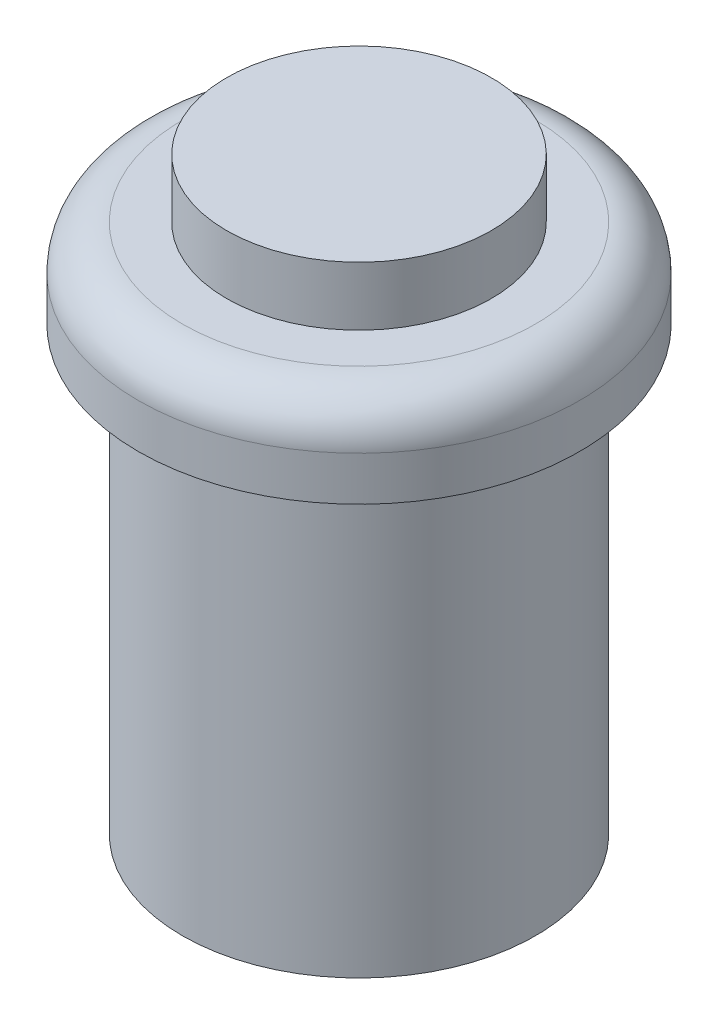
SolidWorks part; units mm, degrees
ref_plane "Front Plane" through (0, 0, 0) normal (0, 0, 1) x (1, 0, 0)
ref_plane "Top Plane" through (0, 0, 0) normal (0, 1, 0) x (1, 0, 0)
ref_plane "Right Plane" through (0, 0, 0) normal (1, 0, 0) x (0, 0, -1)
sketch "Sketch1" plane through (0, 0, 0) normal (0, 1, 0) x (1, 0, 0)
  circle A0 centre (0, 0) radius 6
  dimension "D1" = 12
extrude "Boss-Extrude1" add sketch "Sketch1" along normal blind 15
sketch "Sketch2" plane through (0, 15, 0) normal (0, 1, 0) x (1, 0, 0)
  circle A0 centre (0, 0) radius 7.5
  dimension "D1" = 15
extrude "Boss-Extrude2" add sketch "Sketch2" along normal blind 3
sketch "Sketch3" plane through (0, 18, 0) normal (0, 1, 0) x (1, 0, 0)
  circle A0 centre (0, 0) radius 4.5
  dimension "D1" = 9
extrude "Boss-Extrude3" add sketch "Sketch3" along normal blind 2
fillet "Fillet1" radius 1.5 1 edges at (0, 18, 7.5)
